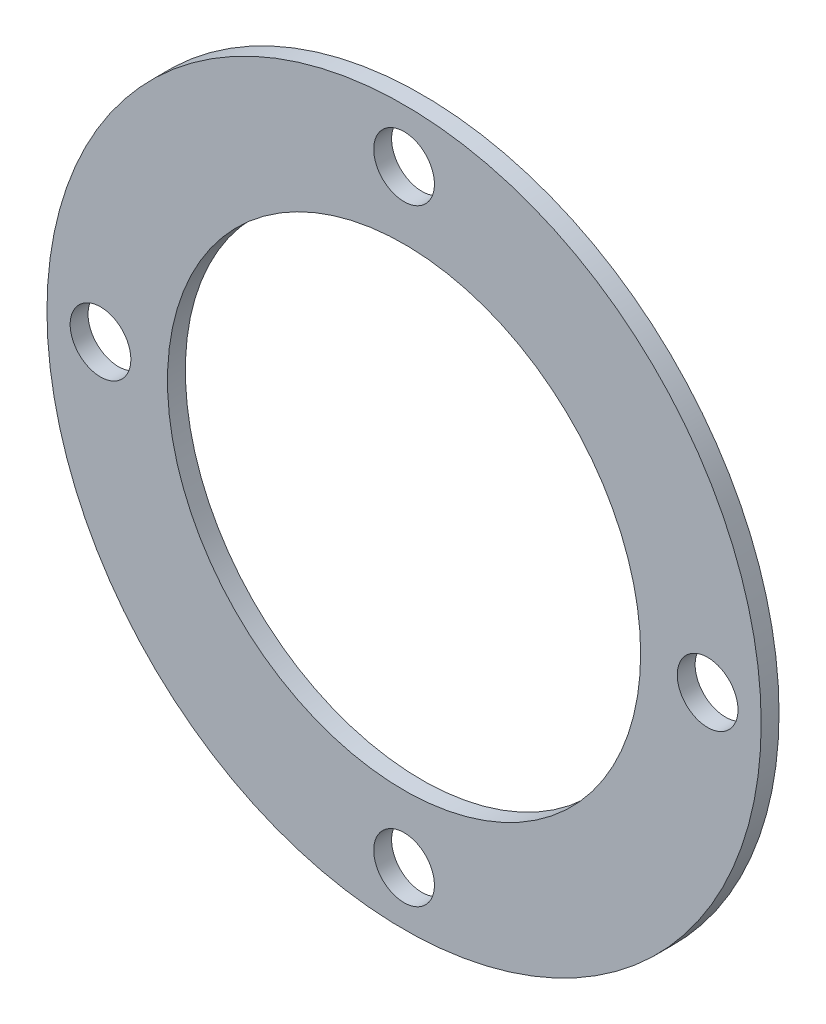
SolidWorks part; units mm, degrees
ref_plane "Front Plane" through (0, 0, 0) normal (0, 0, 1) x (1, 0, 0)
ref_plane "Top Plane" through (0, 0, 0) normal (0, 1, 0) x (1, 0, 0)
ref_plane "Right Plane" through (0, 0, 0) normal (1, 0, 0) x (0, 0, -1)
sketch "Sketch1" plane through (0, 0, 0) normal (0, 0, 1) x (1, 0, 0)
  circle A0 centre (0, 0) radius 20
extrude "Boss-Extrude1" add sketch "Sketch1" along normal blind 1 contours A0
sketch "Sketch2" plane through (0, 0, 1) normal (0, 0, 1) x (1, 0, 0)
  circle A0 centre (0, 0) radius 13.25
extrude "Cut-Extrude1" cut sketch "Sketch2" against normal blind 1
sketch "Sketch3" plane through (0, 0, 1) normal (0, 0, 1) x (1, 0, 0)
  point P0 (0, 17)
  point P2 (17, 0)
  point P4 (0, -17)
  point P6 (-17, 0)
  point P13 (0, 0)
hole_wizard "Tap Drill for M3x0.5 Tap1" positions "Sketch3" profile "Sketch5" hole size "M3x0.5" standard "JIS" end condition through all
sketch "Sketch5" plane through (0, 17, 1) normal (1, 0, 0) x (0, -1, 0)
  line L0 (0, 0) -> (0, 1)
  line L1 (0, 1) -> (1.7, 1)
  line L2 (1.7, 1) -> (1.7, 0)
  line L5 (1.7, 0) -> (0, 0)
  line L11 (0, -6.35) -> (0, 107.95) construction
  dimension "Thru Hole Dia." = 3.4
  dimension "Thru Hole Depth" = 1
